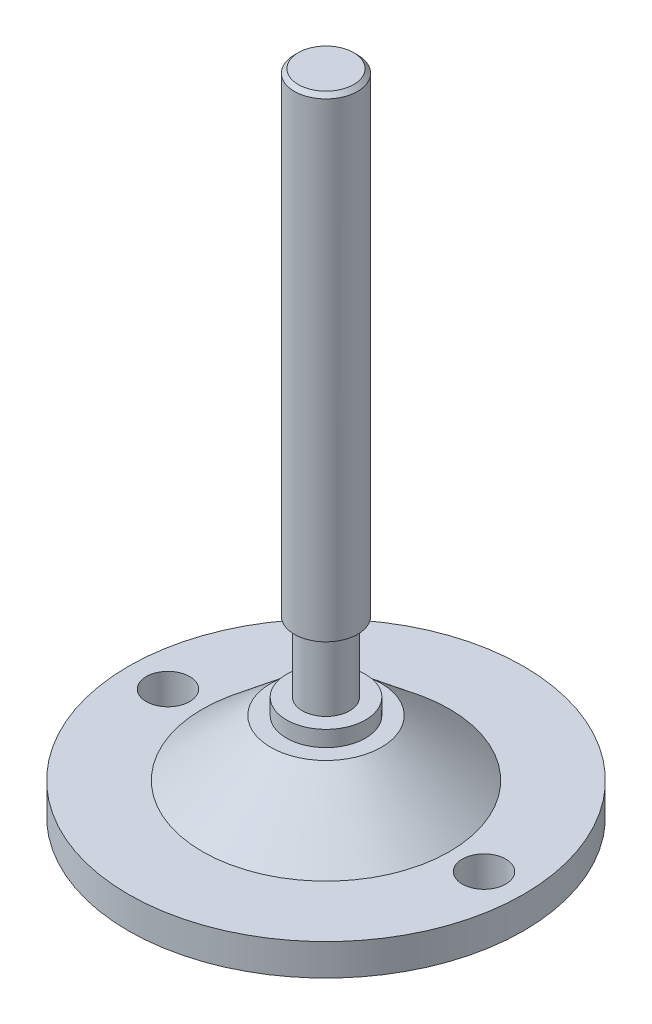
SolidWorks part; units mm, degrees
material "1.4000 (X6Cr13)"
ref_plane "Plan de face" through (0, 0, 0) normal (0, 0, 1) x (1, 0, 0)
ref_plane "Plan de dessus" through (0, 0, 0) normal (0, 1, 0) x (1, 0, 0)
ref_plane "Plan de droite" through (0, 0, 0) normal (1, 0, 0) x (0, 0, -1)
sketch "Esquisse1" plane through (0, 0, 0) normal (0, 0, 1) x (1, 0, 0)
  line L0 (0, 0) -> (0, 90.17) construction
  line L1 (0, 0) -> (25, 0)
  line L2 (25, 0) -> (25, 4)
  line L3 (25, 4) -> (15.6323, 4)
  line L4 (15.6323, 4) -> (7, 11.1187)
  line L5 (7, 11.1187) -> (5, 11.1187)
  line L6 (5, 11.1187) -> (5, 13.1187)
  line L7 (5, 13.1187) -> (3, 13.1187)
  line L8 (3, 13.1187) -> (3, 22)
  line L9 (3, 22) -> (4, 22)
  line L10 (4, 22) -> (4, 82)
  line L11 (4, 82) -> (0, 82)
  line L12 (0, 82) -> (0, 0)
  dimension "D1" = 50
  dimension "D2" = 8
  dimension "D3" = 4
  dimension "D4" = 3
  dimension "D5" = 2
  dimension "D6" = 82
  dimension "D7" = 60
  dimension "D8" = 2
  dimension "D9" = 2
  dimension "D10" = 8.6323
  dimension "D11" = 9.3677
  dimension "D12" = 8.8813
revolve "Révolution1" add sketch "Esquisse1" angle 360 about L0
chamfer "Chanfrein1" distance 0.5 angle 45 1 edges at (0, 82, -4)
sketch "Esquisse2" plane through (0, 0, 0) normal (0, -1, 0) x (1, 0, 0)
  line L0 (-25, 0) -> (25, 0) construction
  circle A0 centre (0, 0) radius 25 construction
  circle A1 centre (0, 0) radius 20 construction
  circle A2 centre (-20, 0) radius 2.75
  circle A3 centre (20, 0) radius 2.75
  dimension "D1" = 5.5
  dimension "D2" = 40
extrude "Enlèv. mat.-Extru.1" cut sketch "Esquisse2" against normal through all
